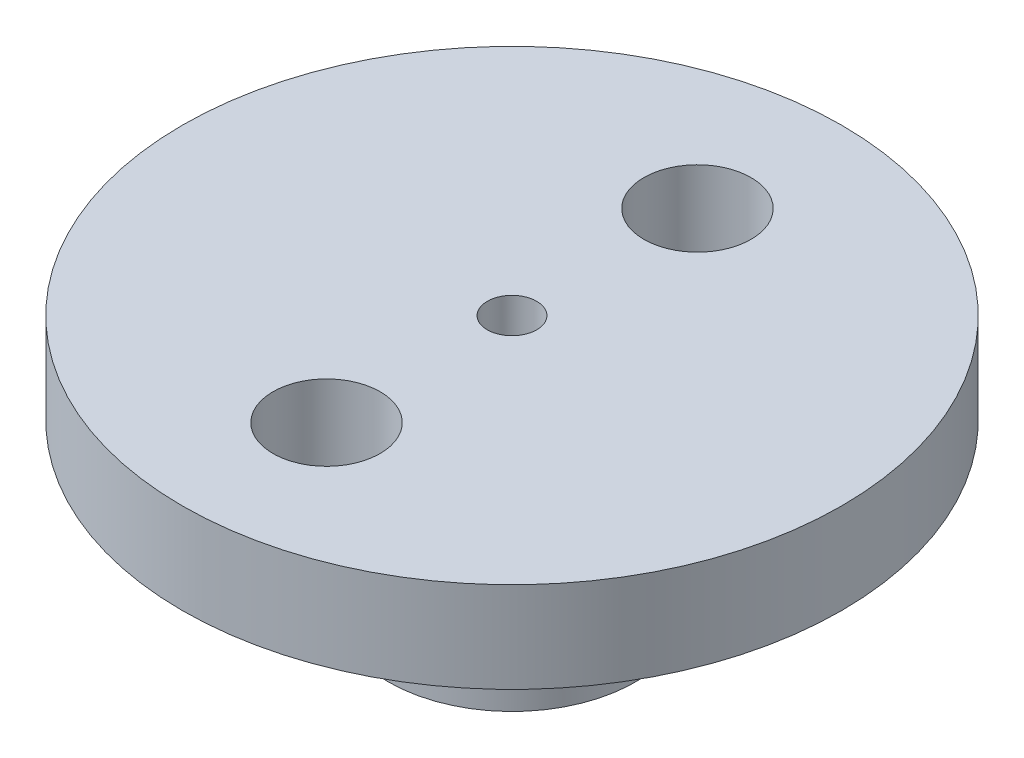
SolidWorks part; units mm, degrees
ref_plane "Front Plane" through (0, 0, 0) normal (0, 0, 1) x (1, 0, 0)
ref_plane "Top Plane" through (0, 0, 0) normal (0, 1, 0) x (1, 0, 0)
ref_plane "Right Plane" through (0, 0, 0) normal (1, 0, 0) x (0, 0, -1)
sketch "Sketch1" plane through (0, 0, 0) normal (0, 1, 0) x (1, 0, 0)
  circle A0 centre (0, 0) radius 8
  dimension "D1" = 16
extrude "Boss-Extrude1" add sketch "Sketch1" along normal blind 2.2
sketch "Sketch2" plane through (0, 2.2, 0) normal (0, 1, 0) x (1, 0, 0)
  line L0 (0, -16.0698) -> (0, 16.0698) construction
  line L1 (-27.9531, 0) -> (27.9531, 0) construction
  circle A2 centre (0, 4.5) radius 1.3
  circle A12 centre (0, -4.5) radius 1.3
  point P3 (0, 0)
  point P9 (0, 0)
  dimension "D1" = 2.6
  dimension "D2" = 4.5
extrude "Cut-Extrude1" cut sketch "Sketch2" against normal blind 2.2
sketch "Sketch3" plane through (0, 0, 0) normal (0, -1, 0) x (1, 0, 0)
  circle A0 centre (0, 0) radius 3
  circle A1 centre (0, 0) radius 2.45
  dimension "D1" = 6
  dimension "D2" = 4.9
extrude "Boss-Extrude2" add sketch "Sketch3" along normal blind 4
sketch "Sketch8" plane through (0, 0, 0) normal (0, -1, 0) x (1, 0, 0)
  circle A0 centre (0, 0) radius 0.6
  dimension "D1" = 1.2
extrude "Cut-Extrude7" cut sketch "Sketch8" against normal up to surface (2.2 mm away) up to face at (0, 2.2, 3.2)
